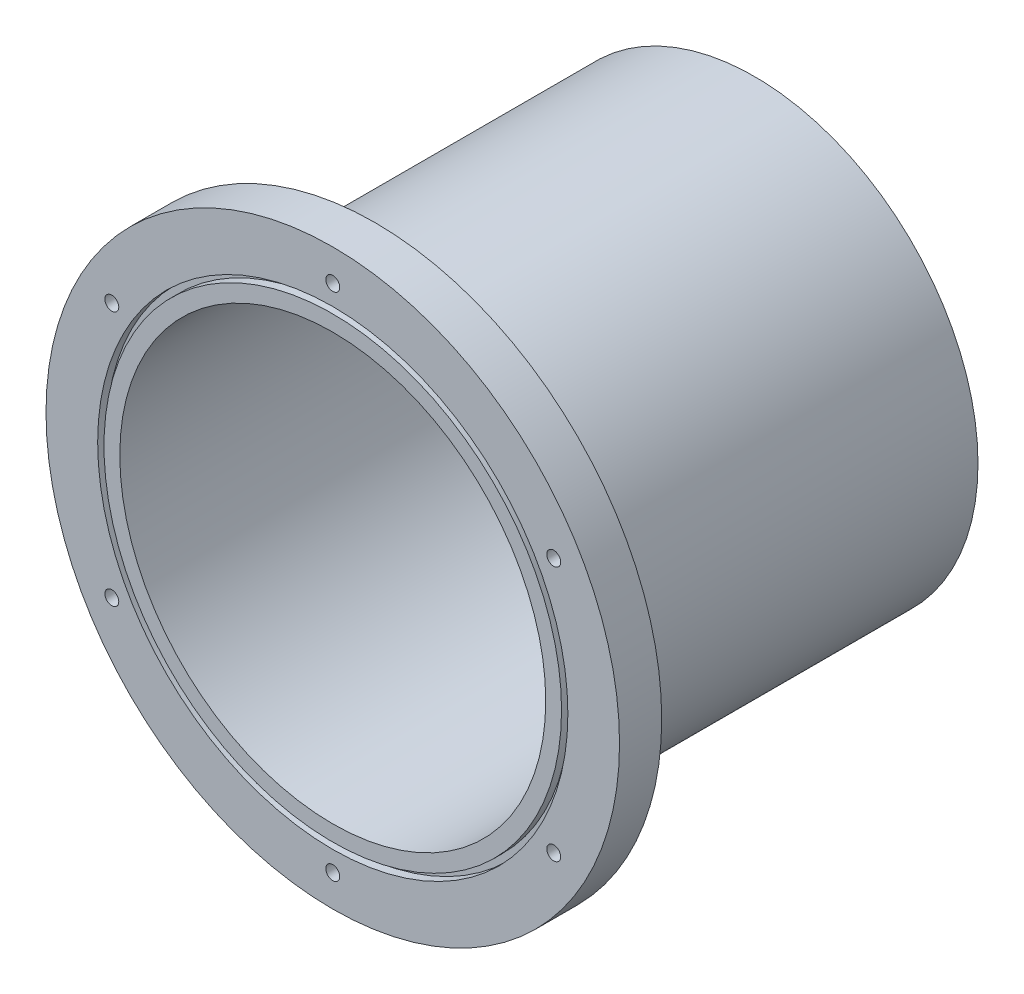
SolidWorks part; units mm, degrees
ref_plane "Front" through (0, 0, 0) normal (0, 0, 1) x (1, 0, 0)
ref_plane "Top" through (0, 0, 0) normal (0, 1, 0) x (1, 0, 0)
ref_plane "Right" through (0, 0, 0) normal (1, 0, 0) x (0, 0, -1)
sketch "Sketch1" plane through (0, 0, 0) normal (0, 0, 1) x (1, 0, 0)
  circle A0 centre (0, 0) radius 101
  circle A1 centre (0, 0) radius 106
  dimension "D1" = 202
  dimension "D2" = 212
extrude "Boss-Extrude1" add sketch "Sketch1" along normal blind 200
ref_plane "Plane1" through (0, 0, 200) normal (0, 0, 1) x (1, 0, 0)
sketch "Sketch3" plane through (0, 0, 200) normal (0, 0, 1) x (1, 0, 0)
  circle A0 centre (0, 0) radius 106
  circle A1 centre (0, 0) radius 136
  dimension "D1" = 272
extrude "Boss-Extrude3" add sketch "Sketch3" against normal blind 20 contours A1 | A0
sketch "Sketch4" plane through (0, 0, 200) normal (0, 0, 1) x (1, 0, 0)
  line L0 (0, 121) -> (0, 136) construction
  circle A0 centre (0, 0) radius 136 construction
  circle A1 centre (0, 121) radius 3.3
  dimension "D1" = 6.6
  dimension "D2" = 15
sketch "Sketch5" plane through (0, 0, 200) normal (0, 0, 1) x (1, 0, 0)
  circle A0 centre (0, 0) radius 108.5
  circle A1 centre (0, 0) radius 111.5
  dimension "D1" = 217
  dimension "D2" = 223
extrude "Cut-Extrude1" cut sketch "Sketch5" against normal blind 4 contours A1 | A0
extrude "Cut-Extrude2" cut sketch "Sketch4" against normal blind 33 contours A1
pattern_circular "CirPattern1" count 6 over 360 about axis through (0, 0, 0) along (0, 0, 1) of "Cut-Extrude2"
